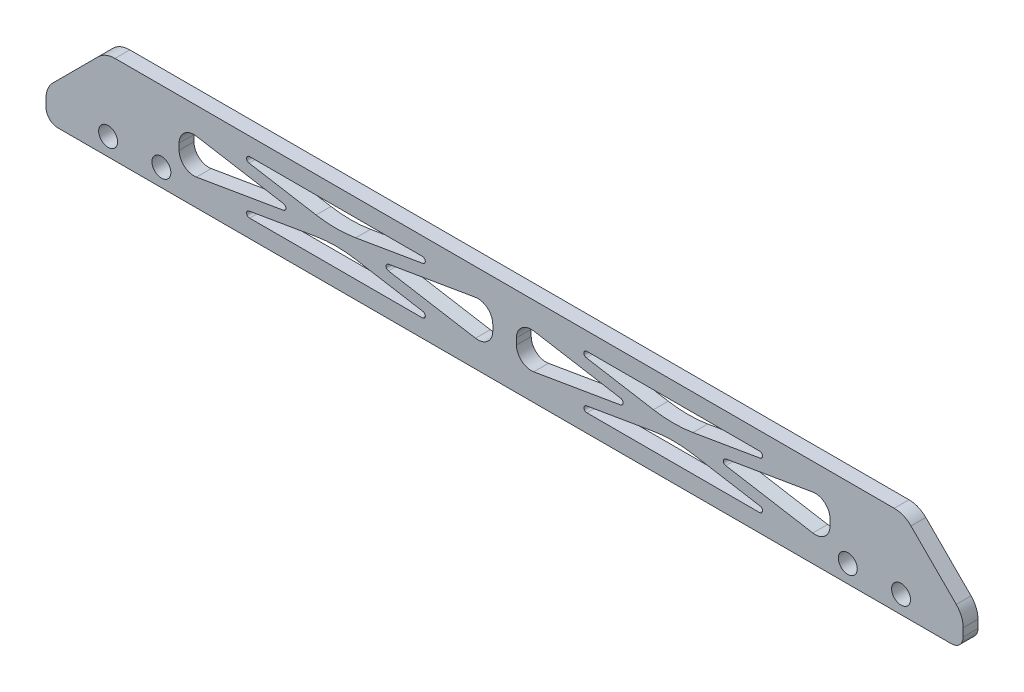
SolidWorks part; units mm, degrees
ref_plane "Front Plane" through (0, 0, 0) normal (0, 0, 1) x (1, 0, 0)
ref_plane "Top Plane" through (0, 0, 0) normal (0, 1, 0) x (1, 0, 0)
ref_plane "Right Plane" through (0, 0, 0) normal (1, 0, 0) x (0, 0, -1)
sketch "Sketch1" plane through (0, 0, 0) normal (0, 0, 1) x (1, 0, 0)
  line L0 (-98.425, -5.715) -> (-73.66, -5.715) construction
  line L1 (-98.425, 9.525) -> (98.425, 9.525)
  line L2 (-98.425, 9.525) -> (-98.425, -9.525)
  line L3 (-98.425, -9.525) -> (98.425, -9.525)
  line L4 (98.425, 9.525) -> (98.425, -9.525)
  line L5 (-98.425, 9.525) -> (98.425, -9.525) construction
  line L6 (-98.425, -9.525) -> (98.425, 9.525) construction
  line L7 (98.425, -5.715) -> (73.66, -5.715) construction
  circle A0 centre (-73.66, -5.715) radius 2.032
  circle A1 centre (-85.09, -5.715) radius 2.032
  circle A2 centre (73.66, -5.715) radius 2.032
  circle A3 centre (85.09, -5.715) radius 2.032
  point P0 (0, 0)
  dimension "D3" = 4.064
  dimension "D7" = 11.43
  dimension "D1" = 19.05
  dimension "D2" = 196.85
  dimension "D4" = 24.765
  dimension "D5" = 11.43
  dimension "D6" = 3.81
extrude "Boss-Extrude1" add sketch "Sketch1" along normal blind 3.175 contours L3 L4 L1 L2 | A1 | A0 | A2 | A3
chamfer "Chamfer1" distance 12.7 angle 45 2 edges at (98.425, 9.525, 1.5875) (-98.425, 9.525, 1.5875)
fillet "Fillet1" radius 5.08 4 edges at (98.425, -3.175, 1.5875) (85.725, 9.525, 1.5875) (-98.425, -3.175, 1.5875) (-85.725, 9.525, 1.5875)
fillet "Fillet2" radius 2.54 2 edges at (-98.425, -9.525, 1.5875) (98.425, -9.525, 1.5875)
sketch "Sketch2" plane through (0, 0, 3.175) normal (0, 0, 1) x (1, 0, 0)
  line L6 (-69.85, -5.715) -> (-69.85, 5.715)
  line L7 (69.85, -5.715) -> (69.85, 5.715)
  line L8 (0, -5.715) -> (0, 5.715) construction
  line L9 (2.54, -5.715) -> (2.54, 5.715)
  line L10 (-2.54, -5.715) -> (-2.54, 5.715)
  line L11 (2.54, -5.715) -> (-2.54, -5.715)
  line L12 (-94.615, -5.2792) -> (-94.615, -5.715)
  line L13 (-94.615, -5.715) -> (94.615, -5.715)
  line L14 (94.615, -5.715) -> (94.615, -5.2792)
  line L15 (94.243, -4.3812) -> (84.5188, 5.343)
  line L16 (83.6208, 5.715) -> (-83.6208, 5.715)
  line L17 (-84.5188, 5.343) -> (-94.243, -4.3812)
  line L18 (-94.615, -5.2792) -> (-94.615, -5.715)
  line L19 (-94.615, -5.715) -> (94.615, -5.715)
  line L20 (94.615, -5.715) -> (94.615, -5.2792)
  line L21 (94.243, -4.3812) -> (84.5188, 5.343)
  line L22 (83.6208, 5.715) -> (-83.6208, 5.715)
  line L23 (-84.5188, 5.343) -> (-94.243, -4.3812)
  line L24 (2.54, 5.715) -> (-2.54, 5.715)
  line L25 (-69.85, 5.715) -> (-2.54, -5.715) construction
  line L26 (-69.85, -5.715) -> (-2.54, 5.715) construction
  line L27 (2.54, 5.715) -> (69.85, -5.715) construction
  line L28 (69.85, 5.715) -> (2.54, -5.715) construction
  line L29 (2.3274, 4.4629) -> (69.6374, -6.9671)
  line L30 (69.6374, 6.9671) -> (2.3274, -4.4629)
  line L31 (-70.0626, 4.4629) -> (-2.7526, -6.9671)
  line L32 (-69.6374, -6.9671) -> (-2.3274, 4.4629)
  line L33 (2.7526, 6.9671) -> (70.0626, -4.4629)
  line L34 (70.0626, 4.4629) -> (2.7526, -6.9671)
  line L35 (-69.6374, 6.9671) -> (-2.3274, -4.4629)
  line L36 (-70.0626, -4.4629) -> (-2.7526, 6.9671)
  circle A6 centre (-73.66, -5.715) radius 2.032 construction
  circle A7 centre (73.66, -5.715) radius 2.032 construction
  arc A8 (2.3274, 4.4629) -> (2.7526, 6.9671) centre (2.54, 5.715) cw
  arc A9 (69.6374, -6.9671) -> (70.0626, -4.4629) centre (69.85, -5.715) ccw
  arc A10 (69.6374, 6.9671) -> (70.0626, 4.4629) centre (69.85, 5.715) cw
  arc A11 (2.3274, -4.4629) -> (2.7526, -6.9671) centre (2.54, -5.715) ccw
  arc A12 (94.615, -5.2792) -> (94.243, -4.3812) centre (93.345, -5.2792) ccw
  arc A13 (84.5188, 5.343) -> (83.6208, 5.715) centre (83.6208, 4.445) ccw
  arc A14 (-83.6208, 5.715) -> (-84.5188, 5.343) centre (-83.6208, 4.445) ccw
  arc A15 (-94.243, -4.3812) -> (-94.615, -5.2792) centre (-93.345, -5.2792) ccw
  arc A16 (94.615, -5.2792) -> (94.243, -4.3812) centre (93.345, -5.2792) ccw
  arc A17 (84.5188, 5.343) -> (83.6208, 5.715) centre (83.6208, 4.445) ccw
  arc A18 (-83.6208, 5.715) -> (-84.5188, 5.343) centre (-83.6208, 4.445) ccw
  arc A19 (-94.243, -4.3812) -> (-94.615, -5.2792) centre (-93.345, -5.2792) ccw
  arc A20 (-70.0626, 4.4629) -> (-69.6374, 6.9671) centre (-69.85, 5.715) cw
  arc A21 (-2.7526, -6.9671) -> (-2.3274, -4.4629) centre (-2.54, -5.715) ccw
  arc A22 (-69.6374, -6.9671) -> (-70.0626, -4.4629) centre (-69.85, -5.715) cw
  arc A23 (-2.3274, 4.4629) -> (-2.7526, 6.9671) centre (-2.54, 5.715) ccw
  dimension "D2" = 3.81
  dimension "D3" = 3.81
  dimension "D4" = 2.54
  dimension "D6" = 1.27
  dimension "D1" = 3.81
  dimension "D5" = 2.54
  dimension "D7" = 1.27
extrude "Cut-Extrude1" cut sketch "Sketch2" against normal up to next contours L35 L36 L22 | L6 L36 L31 | L32 L19 L31 | L32 L35 L10 | L30 L29 L9 | L22 L33 L30 | L7 L34 L33 | L29 L34 L19
fillet "Fillet3" radius 3.175 8 edges at (69.85, -4.4268, 1.5875) (69.85, 4.4268, 1.5875) (2.54, -4.4268, 1.5875) (2.54, 4.4268, 1.5875) (-2.54, -4.4268, 1.5875) (-2.54, 4.4268, 1.5875) (-69.85, 4.4268, 1.5875) (-69.85, -4.4268, 1.5875)
fillet "Fillet4" radius 0.635 12 edges at (62.264, 5.715, 1.5875) (62.264, -5.715, 1.5875) (28.609, 0, 1.5875) (10.126, -5.715, 1.5875) (10.126, 5.715, 1.5875) (43.781, 0, 1.5875) (-62.264, 5.715, 1.5875) (-10.126, 5.715, 1.5875) (-10.126, -5.715, 1.5875) (-62.264, -5.715, 1.5875) (-43.781, 0, 1.5875) (-28.609, 0, 1.5875)
fillet "Fillet5" radius 25.4 4 edges at (-36.195, 1.2882, 1.5875) (-36.195, -1.2882, 1.5875) (36.195, -1.2882, 1.5875) (36.195, 1.2882, 1.5875)
